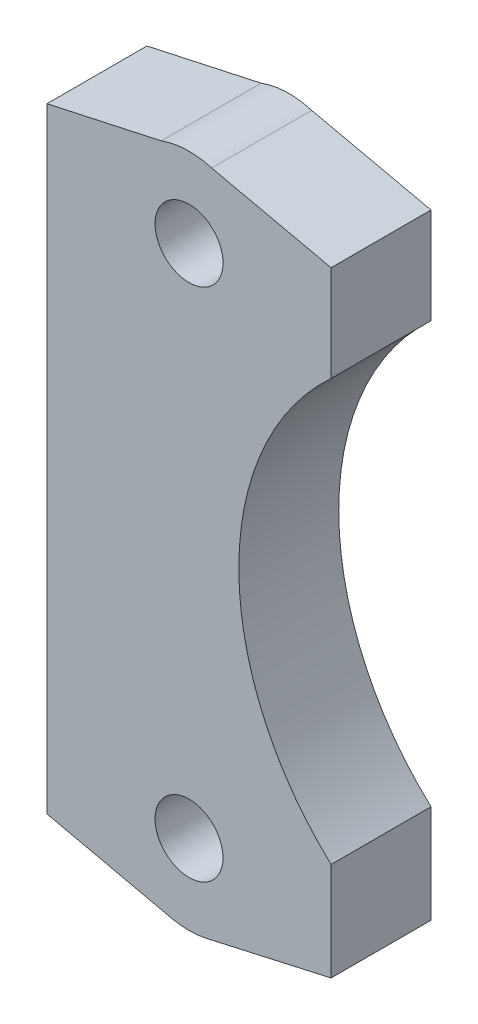
SolidWorks part; units mm, degrees
ref_plane "Front Plane" through (0, 0, 0) normal (0, 0, 1) x (1, 0, 0)
ref_plane "Top Plane" through (0, 0, 0) normal (0, 1, 0) x (1, 0, 0)
ref_plane "Right Plane" through (0, 0, 0) normal (1, 0, 0) x (0, 0, -1)
sketch "Sketch2" plane through (0, 0, 0.0223) normal (0, 0, 1) x (1, 0, 0)
  line L0 (26.8159, -16.7901) -> (20.585, -15.39)
  line L1 (20.585, -15.39) -> (20.585, 15.39)
  line L2 (34.7995, 15.39) -> (20.585, 15.39) construction
  line L3 (20.585, 15.39) -> (26.2984, 16.6365)
  line L4 (34.7995, 15.39) -> (28.8288, 16.7224)
  line L5 (34.7995, -15.39) -> (28.5687, -16.7901)
  line L6 (28.5687, -16.7901) -> (34.7995, -15.39) construction
  line L7 (34.7995, -15.39) -> (34.7995, -10.4696)
  line L9 (34.7995, 10.5897) -> (34.7995, 15.39)
  circle A0 centre (27.6923, -12.89) radius 1.7
  circle A1 centre (27.6923, 12.89) radius 1.7
  arc A2 (28.8288, 16.7224) -> (26.2984, 16.6365) centre (27.6923, 12.89) ccw
  arc A3 (26.8159, -16.7901) -> (28.5687, -16.7901) centre (27.6923, -12.89) ccw
  arc A4 (34.7995, 10.5897) -> (34.7995, -10.4696) centre (44.5, 0.06) ccw
extrude "Boss-Extrude1" add sketch "Sketch2" along normal blind 5
